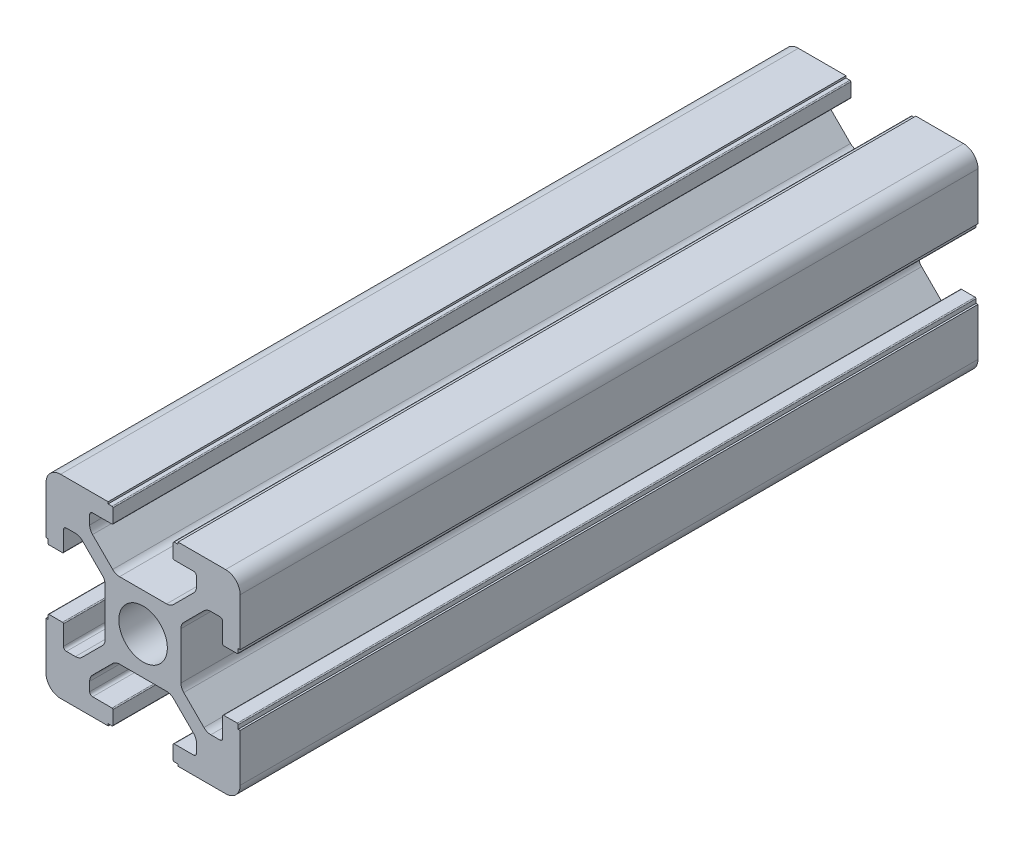
SolidWorks part; units mm, degrees
material "6063-T5"
ref_plane "前视基准面" through (0, 0, 0) normal (0, 0, 1) x (1, 0, 0)
ref_plane "上视基准面" through (0, 0, 0) normal (0, 1, 0) x (1, 0, 0)
ref_plane "右视基准面" through (0, 0, 0) normal (1, 0, 0) x (0, 0, -1)
sketch "草图1" plane through (0, 0, 0) normal (0, 0, 1) x (1, 0, 0)
  line L0 (-1.4389, 10) -> (24.3741, 10) construction
  line L1 (20, 13.6) -> (20, 20)
  line L2 (0, 0) -> (0, 6.4)
  line L3 (0, 20) -> (6.4, 20)
  line L4 (20, 0) -> (20, 6.4)
  line L5 (10, 21.5388) -> (10, -2.4017) construction
  line L6 (6.9, 18.3) -> (6.9, 19.7)
  line L7 (6.8, 18.2) -> (4.8, 18.2)
  line L8 (4.5, 17.9) -> (4.5, 16.9749)
  line L9 (4.7929, 16.2678) -> (6.8678, 14.1929)
  line L10 (7.5749, 13.9) -> (12.4251, 13.9)
  line L11 (6.8, 19.8) -> (6.4, 19.8)
  line L12 (6.4, 19.8) -> (6.4, 20)
  line L13 (0, 13.6) -> (0.2, 13.6)
  line L14 (0.2, 13.6) -> (0.2, 13.2)
  line L15 (0.3, 13.1) -> (1.7, 13.1)
  line L16 (1.8, 13.2) -> (1.8, 15.2)
  line L17 (2.1, 15.5) -> (3.0251, 15.5)
  line L18 (3.7322, 15.2071) -> (5.8071, 13.1322)
  line L19 (6.1, 12.4251) -> (6.1, 7.5749)
  line L20 (13.6, 19.8) -> (13.6, 20)
  line L21 (13.2, 19.8) -> (13.6, 19.8)
  line L22 (13.1, 18.3) -> (13.1, 19.7)
  line L23 (13.2, 18.2) -> (15.2, 18.2)
  line L24 (15.5, 17.9) -> (15.5, 16.9749)
  line L25 (15.2071, 16.2678) -> (13.1322, 14.1929)
  line L26 (0, 6.4) -> (0.2, 6.4)
  line L27 (0.2, 6.4) -> (0.2, 6.8)
  line L28 (0.3, 6.9) -> (1.7, 6.9)
  line L29 (1.8, 6.8) -> (1.8, 4.8)
  line L30 (2.1, 4.5) -> (3.0251, 4.5)
  line L31 (3.7322, 4.7929) -> (5.8071, 6.8678)
  line L32 (13.6, 20) -> (20, 20)
  line L33 (0, 13.6) -> (0, 20)
  line L34 (13.6, 0.2) -> (13.6, 0)
  line L35 (13.2, 0.2) -> (13.6, 0.2)
  line L36 (13.1, 1.7) -> (13.1, 0.3)
  line L37 (13.2, 1.8) -> (15.2, 1.8)
  line L38 (15.5, 2.1) -> (15.5, 3.0251)
  line L39 (15.2071, 3.7322) -> (13.1322, 5.8071)
  line L40 (4.5, 2.1) -> (4.5, 3.0251)
  line L41 (6.8, 1.8) -> (4.8, 1.8)
  line L42 (6.4, 0.2) -> (6.4, 0)
  line L43 (6.8, 0.2) -> (6.4, 0.2)
  line L44 (6.9, 1.7) -> (6.9, 0.3)
  line L45 (4.7929, 3.7322) -> (6.8678, 5.8071)
  line L46 (7.5749, 6.1) -> (12.4251, 6.1)
  line L47 (20, 6.4) -> (19.8, 6.4)
  line L48 (19.8, 6.4) -> (19.8, 6.8)
  line L49 (19.7, 6.9) -> (18.3, 6.9)
  line L50 (18.2, 6.8) -> (18.2, 4.8)
  line L51 (17.9, 4.5) -> (16.9749, 4.5)
  line L52 (16.2678, 4.7929) -> (14.1929, 6.8678)
  line L53 (13.9, 12.4251) -> (13.9, 7.5749)
  line L54 (16.2678, 15.2071) -> (14.1929, 13.1322)
  line L55 (17.9, 15.5) -> (16.9749, 15.5)
  line L56 (18.2, 13.2) -> (18.2, 15.2)
  line L57 (19.7, 13.1) -> (18.3, 13.1)
  line L58 (19.8, 13.6) -> (19.8, 13.2)
  line L59 (20, 13.6) -> (19.8, 13.6)
  line L60 (0, 0) -> (6.4, 0)
  line L61 (13.6, 0) -> (20, 0)
  arc A0 (6.1, 12.4251) -> (5.8071, 13.1322) centre (5.1, 12.4251) ccw
  arc A1 (7.5749, 13.9) -> (6.8678, 14.1929) centre (7.5749, 14.9) cw
  arc A2 (4.5, 16.9749) -> (4.7929, 16.2678) centre (5.5, 16.9749) ccw
  arc A3 (3.7322, 15.2071) -> (3.0251, 15.5) centre (3.0251, 14.5) ccw
  arc A4 (4.5, 17.9) -> (4.8, 18.2) centre (4.8, 17.9) cw
  arc A5 (1.8, 15.2) -> (2.1, 15.5) centre (2.1, 15.2) cw
  arc A6 (0.3, 13.1) -> (0.2, 13.2) centre (0.3, 13.2) cw
  arc A7 (6.9, 19.7) -> (6.8, 19.8) centre (6.8, 19.7) ccw
  arc A8 (1.7, 13.1) -> (1.8, 13.2) centre (1.7, 13.2) ccw
  arc A9 (6.9, 18.3) -> (6.8, 18.2) centre (6.8, 18.3) cw
  arc A10 (13.1, 19.7) -> (13.2, 19.8) centre (13.2, 19.7) cw
  arc A11 (13.1, 18.3) -> (13.2, 18.2) centre (13.2, 18.3) ccw
  arc A12 (15.5, 17.9) -> (15.2, 18.2) centre (15.2, 17.9) ccw
  arc A13 (15.5, 16.9749) -> (15.2071, 16.2678) centre (14.5, 16.9749) cw
  arc A14 (12.4251, 13.9) -> (13.1322, 14.1929) centre (12.4251, 14.9) ccw
  arc A15 (0.3, 6.9) -> (0.2, 6.8) centre (0.3, 6.8) ccw
  arc A16 (1.7, 6.9) -> (1.8, 6.8) centre (1.7, 6.8) cw
  arc A17 (1.8, 4.8) -> (2.1, 4.5) centre (2.1, 4.8) ccw
  arc A18 (3.7322, 4.7929) -> (3.0251, 4.5) centre (3.0251, 5.5) cw
  arc A19 (6.1, 7.5749) -> (5.8071, 6.8678) centre (5.1, 7.5749) cw
  arc A20 (13.1, 0.3) -> (13.2, 0.2) centre (13.2, 0.3) ccw
  arc A21 (13.1, 1.7) -> (13.2, 1.8) centre (13.2, 1.7) cw
  arc A22 (15.5, 2.1) -> (15.2, 1.8) centre (15.2, 2.1) cw
  arc A23 (15.5, 3.0251) -> (15.2071, 3.7322) centre (14.5, 3.0251) ccw
  arc A24 (12.4251, 6.1) -> (13.1322, 5.8071) centre (12.4251, 5.1) cw
  arc A25 (4.5, 2.1) -> (4.8, 1.8) centre (4.8, 2.1) ccw
  arc A26 (6.9, 0.3) -> (6.8, 0.2) centre (6.8, 0.3) cw
  arc A27 (6.9, 1.7) -> (6.8, 1.8) centre (6.8, 1.7) ccw
  arc A28 (4.5, 3.0251) -> (4.7929, 3.7322) centre (5.5, 3.0251) cw
  arc A29 (7.5749, 6.1) -> (6.8678, 5.8071) centre (7.5749, 5.1) ccw
  arc A30 (19.7, 6.9) -> (19.8, 6.8) centre (19.7, 6.8) cw
  arc A31 (18.3, 6.9) -> (18.2, 6.8) centre (18.3, 6.8) ccw
  arc A32 (18.2, 4.8) -> (17.9, 4.5) centre (17.9, 4.8) cw
  arc A33 (16.2678, 4.7929) -> (16.9749, 4.5) centre (16.9749, 5.5) ccw
  arc A34 (13.9, 7.5749) -> (14.1929, 6.8678) centre (14.9, 7.5749) ccw
  arc A35 (13.9, 12.4251) -> (14.1929, 13.1322) centre (14.9, 12.4251) cw
  arc A36 (16.2678, 15.2071) -> (16.9749, 15.5) centre (16.9749, 14.5) cw
  arc A37 (18.2, 15.2) -> (17.9, 15.5) centre (17.9, 15.2) ccw
  arc A38 (18.3, 13.1) -> (18.2, 13.2) centre (18.3, 13.2) cw
  arc A39 (19.7, 13.1) -> (19.8, 13.2) centre (19.7, 13.2) ccw
  circle A40 centre (10, 10) radius 2.5
  point P39 (0.2, 13.1)
  point P42 (6.9, 19.8)
  point P45 (1.8, 13.1)
  point P48 (6.9, 18.2)
  point P66 (10, 13.9)
  point P83 (6.1, 10)
  dimension "D19" = 1
  dimension "D20" = 1
  dimension "D21" = 0.3
  dimension "D22" = 0.1
  dimension "D23" = 5
  dimension "D1" = 20
  dimension "D2" = 20
  dimension "D3" = 10
  dimension "D4" = 10
  dimension "D5" = 1.8
  dimension "D6" = 0.5
  dimension "D7" = 1.6
  dimension "D8" = 3.1
  dimension "D9" = 6.1
  dimension "D10" = 5.5
  dimension "D11" = 3.1
  dimension "D12" = 6.1
  dimension "D13" = 5.5
  dimension "D14" = 1.8
  dimension "D15" = 0.5
  dimension "D16" = 1.5
  dimension "D17" = 45
  dimension "D18" = 1.6
extrude "凸台-拉伸1" add sketch "草图1" along normal blind 76
fillet "圆角1" radius 1.5 4 edges at (20, 0, 38) (0, 0, 38) (0, 20, 38) (20, 20, 38)
